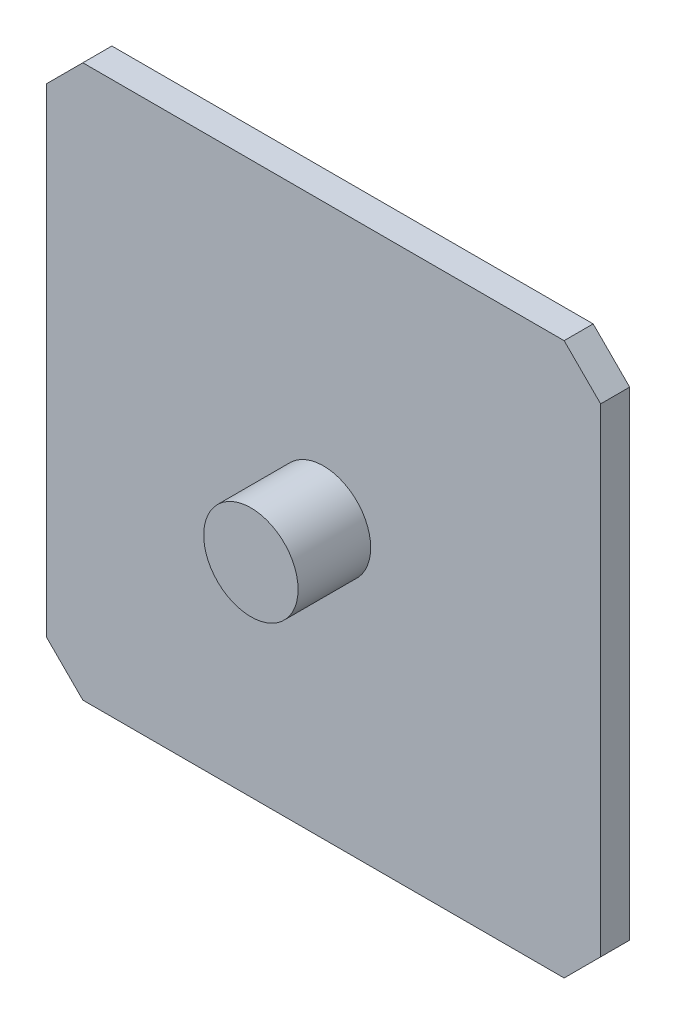
SolidWorks part; units mm, degrees
material "6063-T6"
ref_plane "Front Plane" through (0, 0, 0) normal (0, 0, 1) x (1, 0, 0)
ref_plane "Top Plane" through (0, 0, 0) normal (0, 1, 0) x (1, 0, 0)
ref_plane "Right Plane" through (0, 0, 0) normal (1, 0, 0) x (0, 0, -1)
sketch "Sketch1" plane through (0, 0, 0) normal (0, 0, 1) x (-1, 0, 0)
  line L0 (19.05, 0) -> (-19.05, 0) construction
  line L1 (0, -19.05) -> (0, 19.05) construction
  line L2 (-19.05, 4.9276) -> (-19.05, 16.6878)
  line L3 (-18.044, 4.1656) -> (-19.05, 4.9276)
  line L4 (-15.6692, 4.1656) -> (-18.044, 4.1656)
  line L5 (-14.9297, 6.2238) -> (-14.9074, 4.9409)
  line L6 (-16.256, 8.763) -> (-16.256, 7.7216)
  line L7 (-16.256, -7.7216) -> (-16.256, -8.763)
  line L8 (-14.9074, -4.9409) -> (-14.9297, -6.2238)
  line L9 (-18.044, -4.1656) -> (-15.6692, -4.1656)
  line L10 (-19.05, -4.9276) -> (-18.044, -4.1656)
  line L11 (-19.05, -16.6878) -> (-19.05, -4.9276)
  line L26 (-16.8656, 12.319) -> (-16.8656, 15.6829)
  line L27 (-16.6424, 16.2217) -> (-16.2217, 16.6424)
  line L28 (-15.6829, 16.8656) -> (-12.319, 16.8656)
  line L29 (-11.557, 16.1036) -> (-11.557, 12.319)
  line L30 (-12.319, 11.557) -> (-16.1036, 11.557)
  line L31 (-6.7001, -4.7245) -> (-11.2775, -9.3018)
  line L32 (-11.8163, -9.525) -> (-15.494, -9.525)
  line L34 (-15.494, 9.525) -> (-11.8163, 9.525)
  line L35 (-11.2775, 9.3018) -> (-6.7001, 4.7245)
  line L36 (-5.8074, 2.5692) -> (-5.8074, -2.5692)
  line L37 (-16.1036, -11.557) -> (-12.319, -11.557)
  line L38 (-11.557, -12.319) -> (-11.557, -16.1036)
  line L39 (-12.319, -16.8656) -> (-15.6829, -16.8656)
  line L40 (-16.2217, -16.6424) -> (-16.6424, -16.2217)
  line L41 (-16.8656, -15.6829) -> (-16.8656, -12.319)
  line L42 (15.6829, -16.8656) -> (12.319, -16.8656)
  line L43 (11.557, -16.1036) -> (11.557, -12.319)
  line L44 (12.319, -11.557) -> (16.1036, -11.557)
  line L45 (16.8656, -12.319) -> (16.8656, -15.6829)
  line L46 (16.6424, -16.2217) -> (16.2217, -16.6424)
  line L47 (11.557, 12.319) -> (11.557, 16.1036)
  line L48 (12.319, 16.8656) -> (15.6829, 16.8656)
  line L49 (16.2217, 16.6424) -> (16.6424, 16.2217)
  line L100 (5.8074, -2.5692) -> (5.8074, 2.5692)
  line L101 (6.7001, 4.7245) -> (11.2775, 9.3018)
  line L102 (11.8163, 9.525) -> (15.494, 9.525)
  line L103 (16.256, 8.763) -> (16.256, 7.7216)
  line L104 (14.9297, 6.2238) -> (14.9074, 4.9409)
  line L105 (15.6692, 4.1656) -> (18.044, 4.1656)
  line L106 (18.044, 4.1656) -> (19.05, 4.9276)
  line L107 (19.05, 4.9276) -> (19.05, 16.6878)
  line L108 (19.05, 16.6878) -> (16.6878, 19.05)
  line L109 (16.6878, 19.05) -> (4.9276, 19.05)
  line L110 (4.9276, 19.05) -> (4.1656, 18.044)
  line L111 (4.1656, 18.044) -> (4.1656, 15.6692)
  line L112 (4.9409, 14.9074) -> (6.2238, 14.9297)
  line L113 (7.7216, 16.256) -> (8.763, 16.256)
  line L114 (9.525, 15.494) -> (9.525, 11.8163)
  line L115 (9.3018, 11.2775) -> (4.7245, 6.7001)
  line L116 (2.5692, 5.8074) -> (-2.5692, 5.8074)
  line L117 (-4.7245, 6.7001) -> (-9.3018, 11.2775)
  line L118 (-9.525, 11.8163) -> (-9.525, 15.494)
  line L119 (-8.763, 16.256) -> (-7.7216, 16.256)
  line L120 (-6.2238, 14.9297) -> (-4.9409, 14.9074)
  line L121 (-4.1656, 15.6692) -> (-4.1656, 18.044)
  line L122 (-4.1656, 18.044) -> (-4.9276, 19.05)
  line L123 (-4.9276, 19.05) -> (-16.6878, 19.05)
  line L124 (-16.6878, 19.05) -> (-19.05, 16.6878)
  line L126 (-19.05, -16.6878) -> (-16.6878, -19.05)
  line L127 (-16.6878, -19.05) -> (-4.9276, -19.05)
  line L128 (-4.9276, -19.05) -> (-4.1656, -18.044)
  line L129 (-4.1656, -18.044) -> (-4.1656, -15.6692)
  line L130 (-4.9409, -14.9074) -> (-6.2238, -14.9297)
  line L131 (-7.7216, -16.256) -> (-8.763, -16.256)
  line L132 (-9.525, -15.494) -> (-9.525, -11.8163)
  line L133 (-9.3018, -11.2775) -> (-4.7245, -6.7001)
  line L134 (-2.5692, -5.8074) -> (2.5692, -5.8074)
  line L135 (4.7245, -6.7001) -> (9.3018, -11.2775)
  line L136 (9.525, -11.8163) -> (9.525, -15.494)
  line L137 (8.763, -16.256) -> (7.7216, -16.256)
  line L138 (6.2238, -14.9297) -> (4.9409, -14.9074)
  line L139 (4.1656, -15.6692) -> (4.1656, -18.044)
  line L140 (4.1656, -18.044) -> (4.9409, -19.05)
  line L141 (4.9409, -19.05) -> (16.6878, -19.05)
  line L142 (16.6878, -19.05) -> (19.05, -16.6878)
  line L143 (19.05, -16.6878) -> (19.05, -4.9276)
  line L144 (19.05, -4.9276) -> (18.044, -4.1656)
  line L145 (18.044, -4.1656) -> (15.6692, -4.1656)
  line L146 (14.9074, -4.9409) -> (14.9297, -6.2238)
  line L147 (16.256, -7.7216) -> (16.256, -8.763)
  line L148 (15.494, -9.525) -> (11.8163, -9.525)
  line L149 (11.2775, -9.3018) -> (6.7001, -4.7245)
  line L150 (16.8656, 15.6829) -> (16.8656, 12.319)
  line L151 (16.1036, 11.557) -> (12.319, 11.557)
  arc A0 (-16.256, 8.763) -> (-15.494, 9.525) centre (-15.494, 8.763) cw
  arc A1 (-14.9074, 4.9409) -> (-15.6692, 4.1656) centre (-15.6692, 4.9276) cw
  arc A2 (-15.5928, 6.966) -> (-14.9297, 6.2238) centre (-15.6916, 6.2105) cw
  arc A3 (-15.5928, 6.966) -> (-16.256, 7.7216) centre (-15.494, 7.7216) cw
  arc A4 (-15.494, -9.525) -> (-16.256, -8.763) centre (-15.494, -8.763) cw
  arc A5 (-16.256, -7.7216) -> (-15.5928, -6.966) centre (-15.494, -7.7216) cw
  arc A6 (-14.9297, -6.2238) -> (-15.5928, -6.966) centre (-15.6916, -6.2105) cw
  arc A7 (-15.6692, -4.1656) -> (-14.9074, -4.9409) centre (-15.6692, -4.9276) cw
  arc A27 (-16.6424, 16.2217) -> (-16.8656, 15.6829) centre (-16.1036, 15.6829) ccw
  arc A28 (-15.6829, 16.8656) -> (-16.2217, 16.6424) centre (-15.6829, 16.1036) ccw
  arc A29 (-11.557, 16.1036) -> (-12.319, 16.8656) centre (-12.319, 16.1036) ccw
  arc A30 (-12.319, 11.557) -> (-11.557, 12.319) centre (-12.319, 12.319) ccw
  arc A31 (-16.8656, 12.319) -> (-16.1036, 11.557) centre (-16.1036, 12.319) ccw
  arc A32 (-11.8163, -9.525) -> (-11.2775, -9.3018) centre (-11.8163, -8.763) ccw
  arc A35 (-11.2775, 9.3018) -> (-11.8163, 9.525) centre (-11.8163, 8.763) ccw
  arc A72 (5.8074, -2.5692) -> (6.7001, -4.7245) centre (8.8554, -2.5692) ccw
  arc A73 (6.7001, 4.7245) -> (5.8074, 2.5692) centre (8.8554, 2.5692) ccw
  arc A74 (11.8163, 9.525) -> (11.2775, 9.3018) centre (11.8163, 8.763) ccw
  arc A75 (16.256, 8.763) -> (15.494, 9.525) centre (15.494, 8.763) ccw
  arc A76 (15.5928, 6.966) -> (16.256, 7.7216) centre (15.494, 7.7216) ccw
  arc A77 (15.5928, 6.966) -> (14.9297, 6.2238) centre (15.6916, 6.2105) ccw
  arc A78 (14.9074, 4.9409) -> (15.6692, 4.1656) centre (15.6692, 4.9276) ccw
  arc A79 (4.1656, 15.6692) -> (4.9409, 14.9074) centre (4.9276, 15.6692) ccw
  arc A80 (6.2238, 14.9297) -> (6.966, 15.5928) centre (6.2105, 15.6916) ccw
  arc A81 (7.7216, 16.256) -> (6.966, 15.5928) centre (7.7216, 15.494) ccw
  arc A82 (9.525, 15.494) -> (8.763, 16.256) centre (8.763, 15.494) ccw
  arc A83 (9.3018, 11.2775) -> (9.525, 11.8163) centre (8.763, 11.8163) ccw
  arc A84 (2.5692, 5.8074) -> (4.7245, 6.7001) centre (2.5692, 8.8554) ccw
  arc A85 (-4.7245, 6.7001) -> (-2.5692, 5.8074) centre (-2.5692, 8.8554) ccw
  arc A86 (-9.525, 11.8163) -> (-9.3018, 11.2775) centre (-8.763, 11.8163) ccw
  arc A87 (-8.763, 16.256) -> (-9.525, 15.494) centre (-8.763, 15.494) ccw
  arc A88 (-6.966, 15.5928) -> (-7.7216, 16.256) centre (-7.7216, 15.494) ccw
  arc A89 (-6.966, 15.5928) -> (-6.2238, 14.9297) centre (-6.2105, 15.6916) ccw
  arc A90 (-4.9409, 14.9074) -> (-4.1656, 15.6692) centre (-4.9276, 15.6692) ccw
  arc A91 (-4.1656, -15.6692) -> (-4.9409, -14.9074) centre (-4.9276, -15.6692) ccw
  arc A92 (-6.2238, -14.9297) -> (-6.966, -15.5928) centre (-6.2105, -15.6916) ccw
  arc A93 (-7.7216, -16.256) -> (-6.966, -15.5928) centre (-7.7216, -15.494) ccw
  arc A94 (-9.525, -15.494) -> (-8.763, -16.256) centre (-8.763, -15.494) ccw
  arc A95 (-9.3018, -11.2775) -> (-9.525, -11.8163) centre (-8.763, -11.8163) ccw
  arc A96 (-2.5692, -5.8074) -> (-4.7245, -6.7001) centre (-2.5692, -8.8554) ccw
  arc A97 (4.7245, -6.7001) -> (2.5692, -5.8074) centre (2.5692, -8.8554) ccw
  arc A98 (9.525, -11.8163) -> (9.3018, -11.2775) centre (8.763, -11.8163) ccw
  arc A99 (8.763, -16.256) -> (9.525, -15.494) centre (8.763, -15.494) ccw
  arc A100 (6.966, -15.5928) -> (7.7216, -16.256) centre (7.7216, -15.494) ccw
  arc A101 (6.966, -15.5928) -> (6.2238, -14.9297) centre (6.2105, -15.6916) ccw
  arc A102 (4.9409, -14.9074) -> (4.1656, -15.6692) centre (4.9276, -15.6692) ccw
  arc A103 (15.6692, -4.1656) -> (14.9074, -4.9409) centre (15.6692, -4.9276) ccw
  arc A104 (14.9297, -6.2238) -> (15.5928, -6.966) centre (15.6916, -6.2105) ccw
  arc A105 (16.256, -7.7216) -> (15.5928, -6.966) centre (15.494, -7.7216) ccw
  arc A106 (15.494, -9.525) -> (16.256, -8.763) centre (15.494, -8.763) ccw
  arc A107 (11.2775, -9.3018) -> (11.8163, -9.525) centre (11.8163, -8.763) ccw
  arc A108 (-5.8074, 2.5692) -> (-6.7001, 4.7245) centre (-8.8554, 2.5692) ccw
  arc A109 (-6.7001, -4.7245) -> (-5.8074, -2.5692) centre (-8.8554, -2.5692) ccw
  arc A110 (-11.557, -12.319) -> (-12.319, -11.557) centre (-12.319, -12.319) ccw
  arc A111 (-12.319, -16.8656) -> (-11.557, -16.1036) centre (-12.319, -16.1036) ccw
  arc A112 (-16.2217, -16.6424) -> (-15.6829, -16.8656) centre (-15.6829, -16.1036) ccw
  arc A113 (-16.8656, -15.6829) -> (-16.6424, -16.2217) centre (-16.1036, -15.6829) ccw
  arc A114 (-16.1036, -11.557) -> (-16.8656, -12.319) centre (-16.1036, -12.319) ccw
  circle A115 centre (0, 0) radius 3.3147
  arc A116 (11.557, -16.1036) -> (12.319, -16.8656) centre (12.319, -16.1036) ccw
  arc A117 (12.319, -11.557) -> (11.557, -12.319) centre (12.319, -12.319) ccw
  arc A118 (16.8656, -12.319) -> (16.1036, -11.557) centre (16.1036, -12.319) ccw
  arc A119 (16.6424, -16.2217) -> (16.8656, -15.6829) centre (16.1036, -15.6829) ccw
  arc A120 (15.6829, -16.8656) -> (16.2217, -16.6424) centre (15.6829, -16.1036) ccw
  arc A121 (12.319, 16.8656) -> (11.557, 16.1036) centre (12.319, 16.1036) ccw
  arc A122 (16.2217, 16.6424) -> (15.6829, 16.8656) centre (15.6829, 16.1036) ccw
  arc A123 (16.8656, 15.6829) -> (16.6424, 16.2217) centre (16.1036, 15.6829) ccw
  arc A124 (16.1036, 11.557) -> (16.8656, 12.319) centre (16.1036, 12.319) ccw
  arc A125 (11.557, 12.319) -> (12.319, 11.557) centre (12.319, 12.319) ccw
  dimension "D1" = 6.6294
  dimension "D2" = 38.1
  dimension "D3" = 38.1
sketch "Sketch2" plane through (0, 0, 0) normal (0, 0, 1) x (1, 0, 0)
  line L1 (16.5752, -19.0093) -> (-16.5752, -19.0093)
  line L2 (19.0898, -16.4947) -> (19.0898, 16.4947)
  line L3 (16.5752, 19.0093) -> (-16.5752, 19.0093)
  line L4 (-19.0898, -16.4947) -> (-19.0898, 16.4947)
  line L5 (19.0898, -19.0093) -> (-19.0898, 19.0093) construction
  line L6 (19.0898, 19.0093) -> (-19.0898, -19.0093) construction
  line L7 (16.5752, -19.0093) -> (19.0898, -16.4947)
  line L8 (-16.5752, -19.0093) -> (-19.0898, -16.4947)
  line L9 (-19.0898, 16.4947) -> (-16.5752, 19.0093)
  line L10 (19.0898, 16.4947) -> (16.5752, 19.0093)
extrude "Boss-Extrude1" add sketch "Sketch2" along normal blind 2
sketch "Sketch3" plane through (0, 0, 2) normal (0, 0, 1) x (1, 0, 0)
  circle A0 centre (0, 0) radius 3.2512
extrude "Boss-Extrude2" add sketch "Sketch3" along normal blind 5
